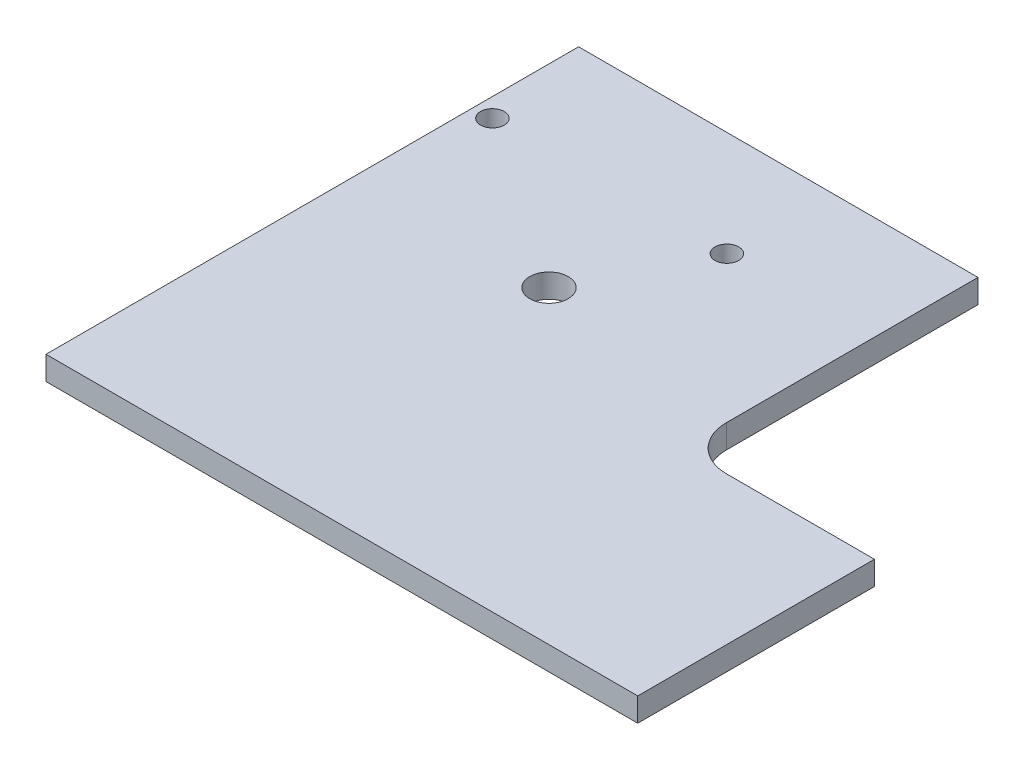
SolidWorks part; units mm, degrees
ref_plane "Front Plane" through (0, 0, 0) normal (0, 0, 1) x (1, 0, 0)
ref_plane "Top Plane" through (0, 0, 0) normal (0, 1, 0) x (1, 0, 0)
ref_plane "Right Plane" through (0, 0, 0) normal (1, 0, 0) x (0, 0, -1)
sketch "Sketch1" plane through (0, 0, 0) normal (0, 1, 0) x (1, 0, 0)
  line L2 (-13.5, -10) -> (-13.5, 10)
  line L3 (-13.5, 10) -> (13.5, 10)
  line L4 (13.5, -10) -> (13.5, 10)
  line L5 (-13.5, -10) -> (13.5, 10) construction
  line L6 (-13.5, 10) -> (13.5, -10) construction
  line L7 (26.5, -26) -> (-13.5, -26)
  line L8 (26.5, -26) -> (26.5, -10)
  line L9 (26.5, -10) -> (13.5, -10)
  line L10 (-13.5, -26) -> (-13.5, -10)
  line L11 (26.5, -26) -> (-13.5, -10) construction
  line L12 (26.5, -10) -> (-13.5, -26) construction
  point P0 (0, 0)
  point P6 (6.5, -18)
  point P11 (6.5, -18)
  point P16 (-18.3401, -24.6905)
  point P17 (0, 0)
  point P18 (7.2991, -17.25)
  point P19 (-6.9308, -9.2704)
  dimension "D1" = 27
  dimension "D2" = 20
  dimension "D7" = 40
  dimension "D8" = 16
extrude "Boss-Extrude1" add sketch "Sketch1" along normal blind 1.6
fillet "Fillet1" radius 3 1 edges at (13.5, 0.8, 10)
hole_wizard "M2 Clearance Hole1" positions "Sketch2" profile "Sketch3" hole size "M2" standard "ANSI Metric" end condition through all
sketch "Sketch2" plane through (0, 1.6, 0) normal (0, 1, 0) x (1, 0, 0)
  line L0 (-13.5, 10) -> (-13.5, -26) construction
  line L1 (13.5, 10) -> (-13.5, 10) construction
  point P0 (-0.4, -5.1)
  dimension "D1" = 13.1
  dimension "D2" = 15.1
sketch "Sketch3" plane through (-0.4, 1.6, 5.1) normal (1, 0, 0) x (0, 0, 1)
  line L0 (0, 0) -> (0, 1.6)
  line L1 (0, 1.6) -> (1.3, 1.6)
  line L2 (1.3, 1.6) -> (1.3, 0)
  line L5 (1.3, 0) -> (0, 0)
  line L11 (0, -6.35) -> (0, 107.95) construction
  dimension "Thru Hole Dia." = 2.6
  dimension "Thru Hole Depth" = 1.6
sketch "Sketch5" plane through (0, 1.6, 0) normal (0, 1, 0) x (1, 0, 0)
  line L5 (-13.5, 10) -> (-13.5, -26) construction
  line L8 (-12.225, 2.9) -> (3.625, 2.9) construction
  line L9 (13.5, 10) -> (-13.5, 10) construction
  circle A0 centre (-12.225, 2.9) radius 0.8
  circle A5 centre (3.625, 2.9) radius 0.8
  point P23 (-4.3, 2.9)
  dimension "D1" = 1.6
  dimension "D4" = 15.85
  dimension "D5" = 9.2
  dimension "D6" = 7.1
extrude "Cut-Extrude1" cut sketch "Sketch5" against normal through all both and the other way through all
sketch "Sketch6" plane through (0, 0, 0) normal (0, -1, 0) x (1, 0, 0)
  circle A0 centre (-0.4, 5.1) radius 3
  circle A1 centre (-0.4, 5.1) radius 1.3 construction
  dimension "D1" = 6
extrude "Cut-Extrude2" cut sketch "Sketch6" against normal blind 0.001
